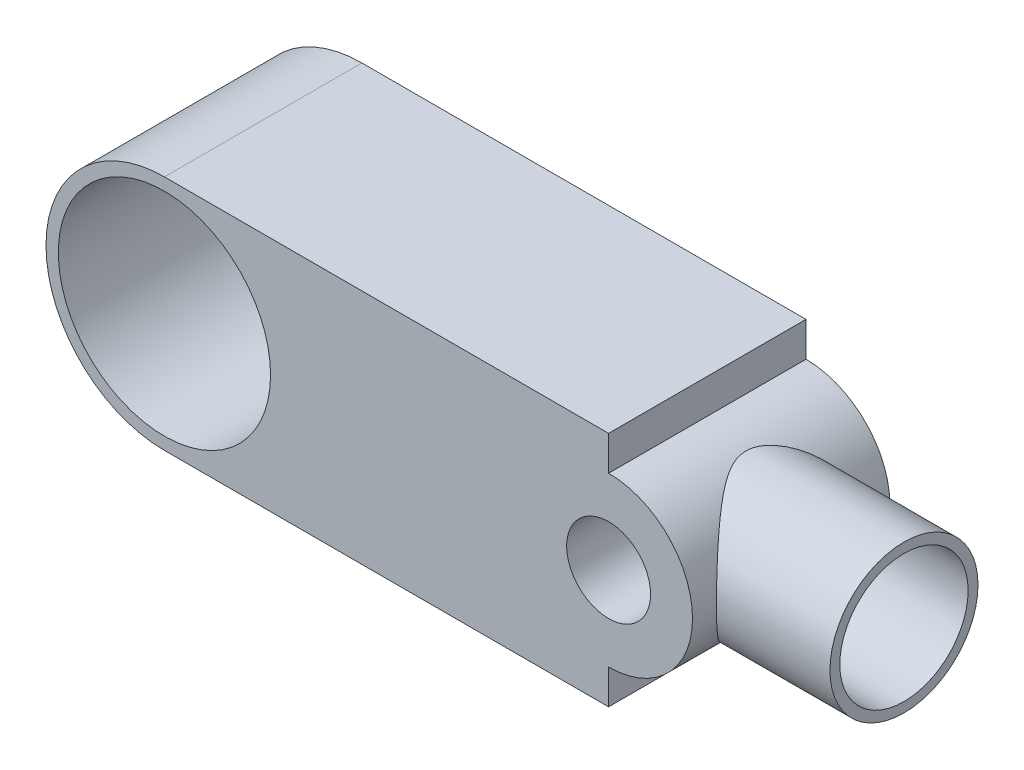
SolidWorks part; units mm, degrees
ref_plane "Front Plane" through (0, 0, 0) normal (0, 0, 1) x (1, 0, 0)
ref_plane "Top Plane" through (0, 0, 0) normal (0, 1, 0) x (1, 0, 0)
ref_plane "Right Plane" through (0, 0, 0) normal (1, 0, 0) x (0, 0, -1)
sketch "Sketch1" plane through (0, 0, 0) normal (0, 0, 1) x (1, 0, 0)
  circle A1 centre (0, 0) radius 17
  dimension "D1" = 34
extrude "Boss-Extrude2" add sketch "Sketch1" along normal blind 40
sketch "Sketch2" plane through (0, 0, 40) normal (0, 0, 1) x (1, 0, 0)
  circle A0 centre (0, 0) radius 8.5
  dimension "D1" = 17
extrude "Cut-Extrude1" cut sketch "Sketch2" against normal blind 38
sketch "Sketch3" plane through (0, 0, 0) normal (0, 0, -1) x (-1, 0, 0)
  circle A0 centre (0, 0) radius 8.5
  dimension "D1" = 17
extrude "Cut-Extrude2" cut sketch "Sketch3" against normal blind 38
sketch "Sketch4" plane through (0, 0, 0) normal (1, 0, 0) x (0, 0, -1)
  line L0 (-48.5184, 0) -> (8.2214, 0) construction
  circle A0 centre (-20.1485, 0) radius 13
  circle A1 centre (-20.1485, 0) radius 15
  dimension "D1" = 30
  dimension "D2" = 26
extrude "Boss-Extrude3" add sketch "Sketch4" along normal blind 40
sketch "Sketch6" plane through (0, 0, 0) normal (0, 0, -1) x (-1, 0, 0)
  circle A0 centre (0, 0) radius 8.5
extrude "Cut-Extrude4" cut sketch "Sketch6" against normal blind 50
ref_plane "Plane1" through (0, 0, 40) normal (0, 0, 1) x (1, 0, 0)
sketch "Sketch9" plane through (0, 0, 40) normal (0, 0, 1) x (1, 0, 0)
  line L0 (-90, -24) -> (0, -24)
  line L1 (0, -24) -> (0, -17)
  line L2 (-90, 24) -> (0, 24)
  line L3 (0, 24) -> (0, 17)
  arc A0 (-90, 24) -> (-90, -24) centre (-90, 0) ccw
  circle A1 centre (0, 0) radius 17 construction
  arc A2 (16.2572, 4.9703) -> (0, -17) centre (0, 0) ccw
  circle A3 centre (0, 0) radius 17
  arc A4 (16.2572, 4.9703) -> (0, 17) centre (0, 0) ccw
  dimension "D1" = 48
  dimension "D2" = 90
  dimension "D3" = 0
extrude "Boss-Extrude4" add sketch "Sketch9" against normal blind 40 contours A2 L3 L2 A0 L0 L1
sketch "Sketch11" plane through (0, 0, 40) normal (0, 0, 1) x (1, 0, 0)
  circle A0 centre (-90, 0) radius 21.5
  dimension "D1" = 43
extrude "Cut-Extrude5" cut sketch "Sketch11" against normal blind 35
sketch "Sketch12" plane through (0, 0, 5) normal (0, 0, 1) x (1, 0, 0)
  circle A0 centre (-90, 0) radius 5
extrude "Cut-Extrude6" cut sketch "Sketch12" against normal through all
